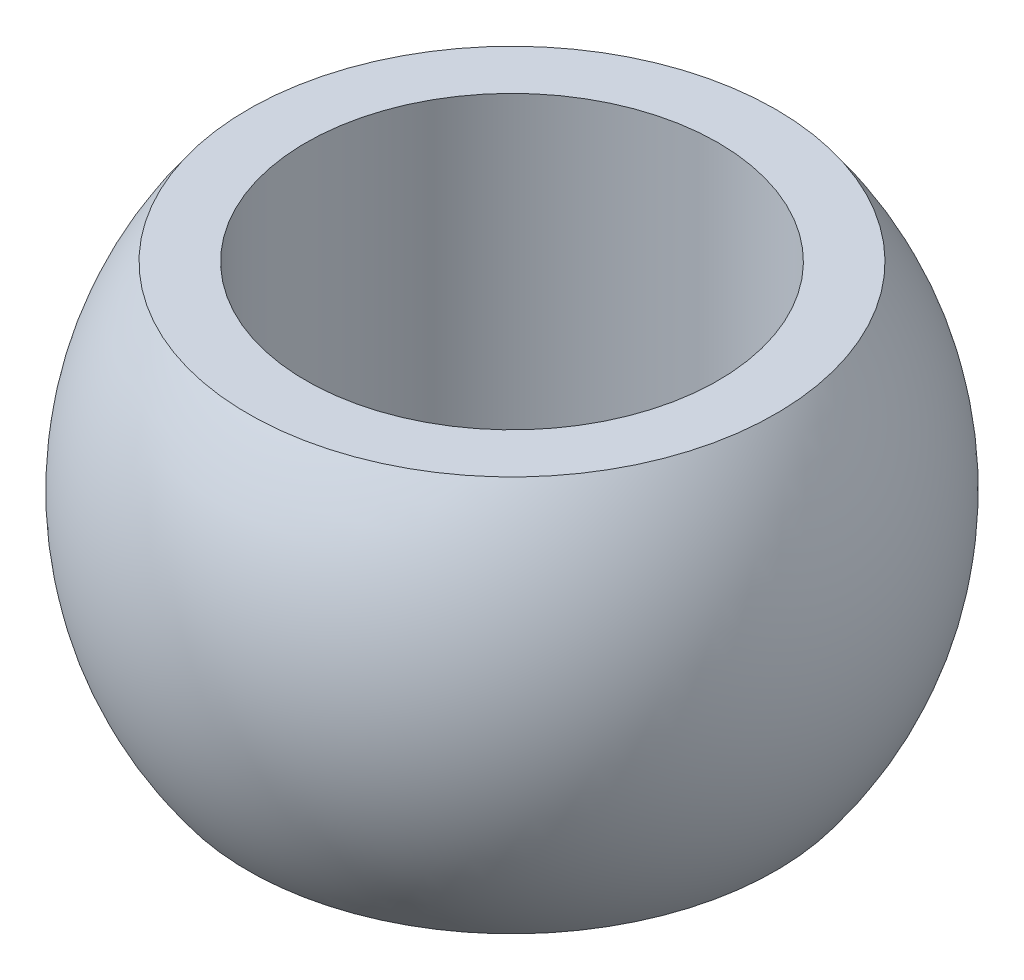
SolidWorks part; units mm, degrees
ref_plane "Front" through (0, 0, 0) normal (0, 0, 1) x (1, 0, 0)
ref_plane "Top" through (0, 0, 0) normal (0, 1, 0) x (1, 0, 0)
ref_plane "Right" through (0, 0, 0) normal (1, 0, 0) x (0, 0, -1)
sketch "Sketch1" plane through (0, 0, 0) normal (1, 0, 0) x (0, 0, -1)
  line L0 (0, 3) -> (0, -3)
  line L1 (0, -3) -> (4, -3)
  line L2 (0, 3) -> (4, 3)
  arc A0 (4, -3) -> (4, 3) centre (0, 0) ccw
  point P7 (0, 0)
  dimension "D1" = 10
  dimension "D2" = 6
revolve "Revolve1" add sketch "Sketch1" angle 360 about L0
sketch "Sketch2" plane through (0, -3, 0) normal (0, -1, 0) x (1, 0, 0)
  circle A0 centre (0, 0) radius 3.125
  dimension "D1" = 6.25
extrude "Cut-Extrude1" cut sketch "Sketch2" against normal through all
